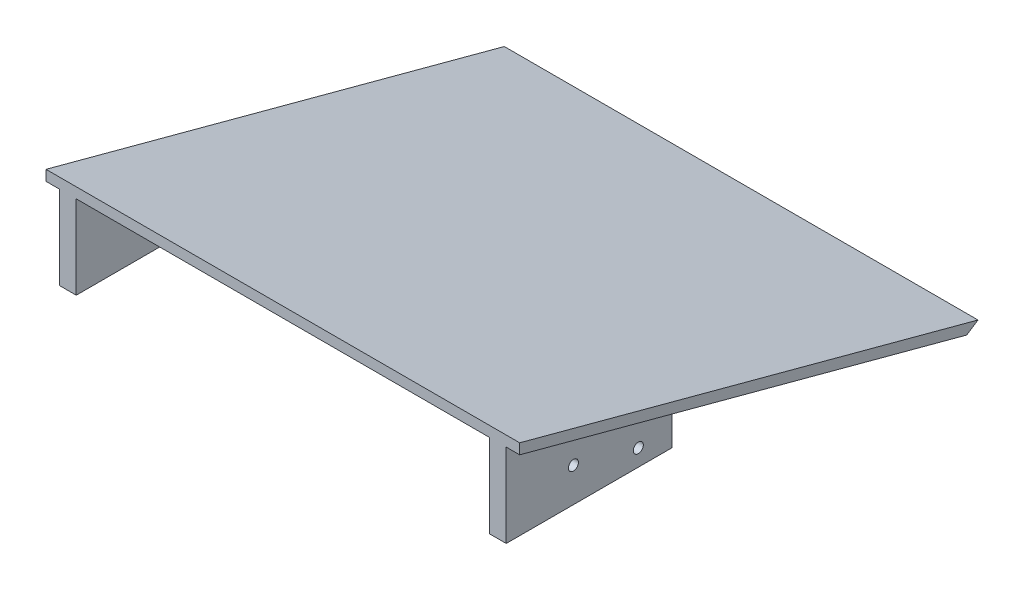
SolidWorks part; units mm, degrees
ref_plane "Front Plane" through (0, 0, 0) normal (0, 0, 1) x (1, 0, 0)
ref_plane "Top Plane" through (0, 0, 0) normal (0, 1, 0) x (1, 0, 0)
ref_plane "Right Plane" through (0, 0, 0) normal (1, 0, 0) x (0, 0, -1)
sketch "Sketch1" plane through (0, 0, 0) normal (1, 0, 0) x (0, 0, -1)
  line L0 (0, 0) -> (133.0466, -35.6497)
  line L1 (133.0466, -35.6497) -> (136.4323, -33.4511)
  line L2 (136.4323, -33.4511) -> (0, 3.1058)
  line L3 (0, 3.1058) -> (0, 0)
  dimension "D1" = 137.74
  dimension "D2" = 105
  dimension "D3" = 132
  dimension "D4" = 3
extrude "Boss-Extrude1" add sketch "Sketch1" along normal mid plane 141
ref_plane "Plane1" through (-66.5, 0, 0) normal (-1, 0, 0) x (0, 0, 1)
sketch "Sketch2" plane through (-66.5, 0, 0) normal (-1, 0, 0) x (0, 0, 1)
  line L0 (0, 0) -> (0, -24.8529)
  line L1 (0, -24.8529) -> (-49.3185, -24.8529)
  line L2 (-49.3185, -24.8529) -> (-49.3185, -13.2149)
  line L3 (0, 0) -> (-133.0466, -35.6497) construction
  line L4 (-49.3185, -13.2149) -> (0, 0)
  line L5 (0, -9.3175) -> (-39.3185, -19.8529) construction
  line L6 (-20, -14.6765) -> (0, -14.6765) construction
  circle A0 centre (-20, -14.6765) radius 1.5
  circle A1 centre (-39.3185, -19.8529) radius 1.5
  dimension "D1" = 20
  dimension "D2" = 20
  dimension "D4" = 3
  dimension "D5" = 5
  dimension "D3" = 9
  dimension "D6" = 10
extrude "Boss-Extrude2" add sketch "Sketch2" against normal blind 5
mirror "Mirror1" about plane through (0, 0, 0) normal (1, 0, 0) of "Boss-Extrude2"
sketch "Sketch3" plane through (0, 0, 0) normal (1, 0, 0) x (0, 0, -1)
  line L0 (0, 0) -> (0, -47.76) construction
  line L1 (0, -47.76) -> (-28.49, -47.76) construction
  line L2 (-28.49, -47.76) -> (-28.49, 37.24) construction
  dimension "D1" = 47.76
  dimension "D2" = 85
  dimension "D3" = 28.49
